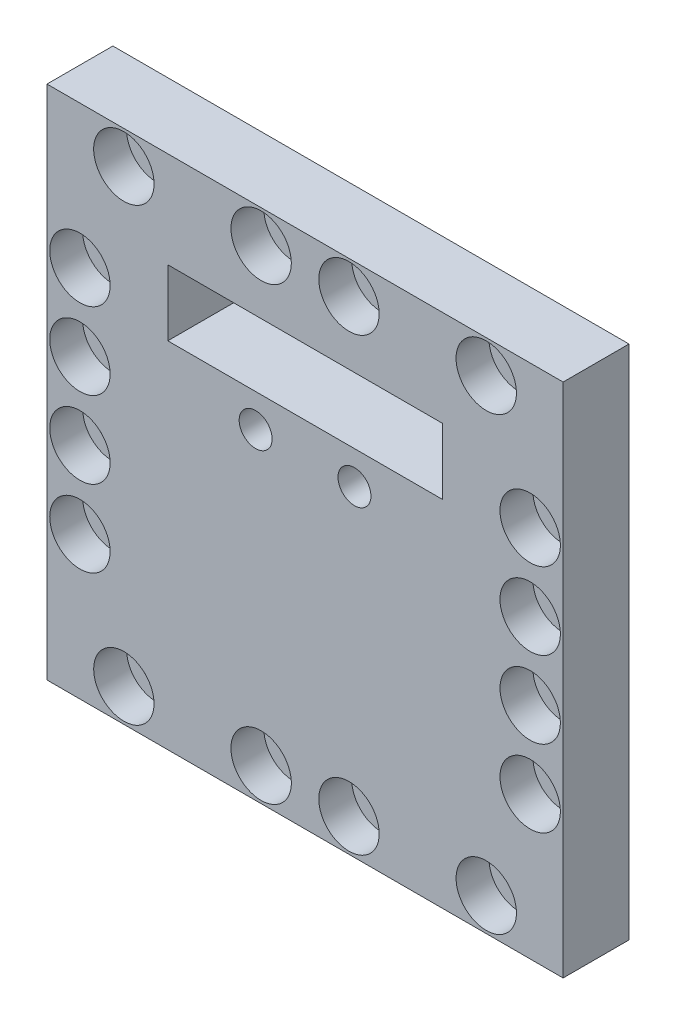
SolidWorks part; units mm, degrees
ref_plane "前视基准面" through (0, 0, 0) normal (0, 0, 1) x (1, 0, 0)
ref_plane "上视基准面" through (0, 0, 0) normal (0, 1, 0) x (1, 0, 0)
ref_plane "右视基准面" through (0, 0, 0) normal (1, 0, 0) x (0, 0, -1)
sketch "草图1" plane through (0, 0, 0) normal (0, 0, 1) x (1, 0, 0)
  line L0 (-41, 21) -> (-41, 7) construction
  line L1 (-47, -47) -> (47, -47)
  line L2 (-47, -47) -> (-47, 47)
  line L3 (-47, 47) -> (47, 47)
  line L4 (47, -47) -> (47, 47)
  line L5 (-47, -47) -> (47, 47) construction
  line L6 (-47, 47) -> (47, -47) construction
  line L7 (0, 26.7258) -> (0, 0) construction
  line L8 (0, 0) -> (29.7837, 0) construction
  line L10 (-25, 17.5) -> (25, 17.5)
  line L11 (-25, 17.5) -> (-25, 29.5)
  line L12 (-25, 29.5) -> (25, 29.5)
  line L13 (25, 17.5) -> (25, 29.5)
  line L14 (-25, 17.5) -> (25, 29.5) construction
  line L15 (-25, 29.5) -> (25, 17.5) construction
  circle A0 centre (-33, 41) radius 3
  circle A1 centre (-8, 41) radius 3
  circle A2 centre (-41, 21) radius 3
  circle A3 centre (-41, 7) radius 3
  circle A4 centre (-41, -7) radius 3
  circle A5 centre (-41, -21) radius 3
  circle A6 centre (-8, -41) radius 3
  circle A7 centre (-33, -41) radius 3
  circle A8 centre (33, -41) radius 3
  circle A9 centre (8, -41) radius 3
  circle A10 centre (41, -21) radius 3
  circle A11 centre (41, -7) radius 3
  circle A12 centre (41, 7) radius 3
  circle A13 centre (41, 21) radius 3
  circle A14 centre (8, 41) radius 3
  circle A15 centre (33, 41) radius 3
  circle A16 centre (-9, 11.5) radius 3
  circle A17 centre (9, 11.5) radius 3
  point P0 (0, 0)
  point P43 (0, 23.5)
  dimension "D3" = 6
  dimension "D4" = 6
  dimension "D5" = 6
  dimension "D8" = 6
  dimension "D17" = 6
  dimension "D18" = 6
  dimension "D1" = 94
  dimension "D2" = 94
  dimension "D6" = 6
  dimension "D7" = 25
  dimension "D9" = 6
  dimension "D10" = 26
  dimension "D12" = 14
  dimension "D13" = 14
  dimension "D14" = 12
  dimension "D15" = 50
  dimension "D16" = 23.5
  dimension "D19" = 6
  dimension "D20" = 6
  dimension "D21" = 9
  dimension "D22" = 9
  dimension "D11" = 4
extrude "凸台-拉伸1" add sketch "草图1" along normal blind 12
sketch "草图2" plane through (0, 0, 12) normal (0, 0, 1) x (1, 0, 0)
  line L0 (0, 21.8115) -> (0, 0) construction
  line L1 (0, 0) -> (25.1023, 0) construction
  circle A2 centre (-33, 41) radius 5.5
  circle A3 centre (-33, 41) radius 5.5
  circle A5 centre (-8, 41) radius 5.5
  circle A6 centre (-8, 41) radius 5.5
  circle A8 centre (-41, 21) radius 5.5
  circle A9 centre (-41, 21) radius 5.5
  circle A10 centre (41, 7) radius 5.5
  circle A11 centre (-41, 7) radius 5.5
  circle A12 centre (-41, 7) radius 5.5
  circle A13 centre (41, 21) radius 5.5
  circle A14 centre (8, 41) radius 5.5
  circle A15 centre (33, 41) radius 5.5
  circle A16 centre (33, -41) radius 5.5
  circle A17 centre (8, -41) radius 5.5
  circle A18 centre (41, -21) radius 5.5
  circle A19 centre (-41, -7) radius 5.5
  circle A20 centre (41, -7) radius 5.5
  circle A21 centre (-41, -21) radius 5.5
  circle A22 centre (-8, -41) radius 5.5
  circle A23 centre (-33, -41) radius 5.5
  dimension "D1" = 2.5
  dimension "D2" = 2.5
  dimension "D3" = 2.5
  dimension "D4" = 2.5
extrude "切除-拉伸1" cut sketch "草图2" against normal blind 6
